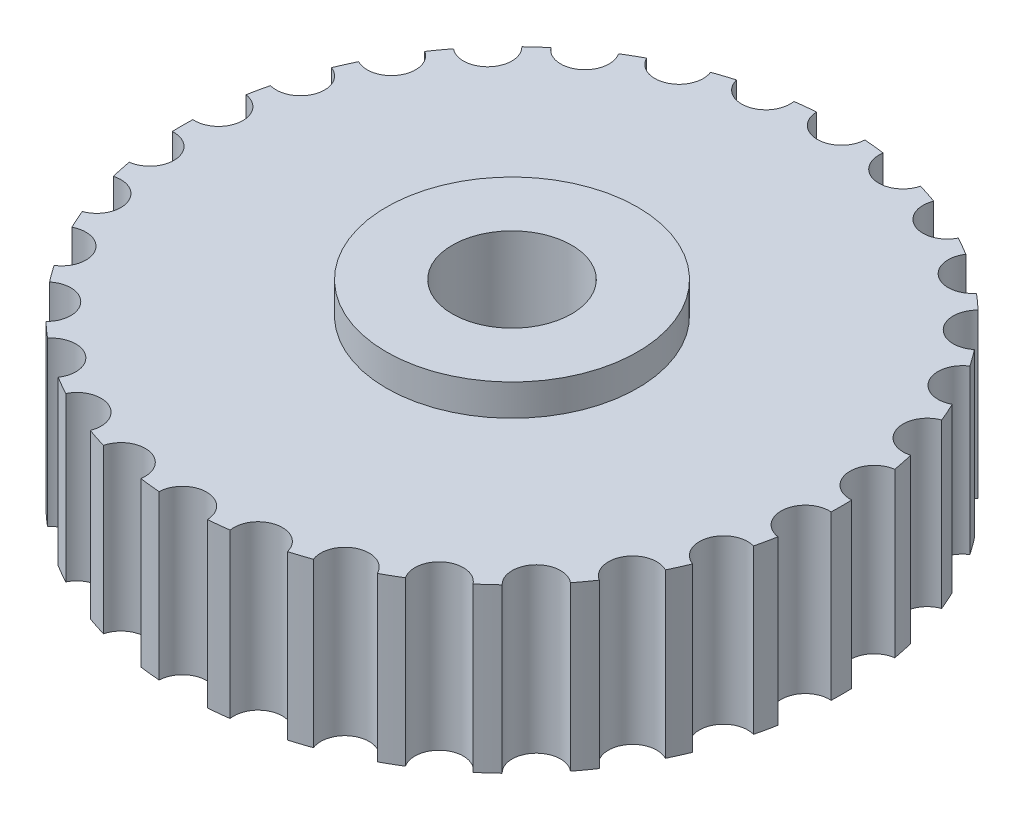
SolidWorks part; units mm, degrees
ref_plane "Спереди" through (0, 0, 0) normal (0, 0, 1) x (1, 0, 0)
ref_plane "Сверху" through (0, 0, 0) normal (0, 1, 0) x (1, 0, 0)
ref_plane "Справа" through (0, 0, 0) normal (1, 0, 0) x (0, 0, -1)
sketch "Эскиз1" plane through (0, 0, 0) normal (0, 1, 0) x (1, 0, 0)
  circle A0 centre (0, 0) radius 10.5
extrude "Бобышка-Вытянуть1" add sketch "Эскиз1" along normal blind 5.2
sketch "Эскиз2" plane through (0, 5.2, 0) normal (0, 1, 0) x (1, 0, 0)
  circle A0 centre (0, 0) radius 1.9
extrude "Вырез-Вытянуть1" cut sketch "Эскиз2" against normal through all
sketch "Эскиз3" plane through (0, 5.2, 0) normal (0, 1, 0) x (1, 0, 0)
  circle A0 centre (0, 0) radius 1.9
  circle A1 centre (0, 0) radius 4
extrude "Бобышка-Вытянуть2" add sketch "Эскиз3" along normal blind 1
sketch "Эскиз4" plane through (0, 5.2, 0) normal (0, 1, 0) x (1, 0, 0)
  line L0 (0, 0) -> (0, 10.5) construction
  circle A0 centre (0, 0) radius 10.5 construction
  circle A1 centre (0, 10.5) radius 0.7714
  circle A2 centre (2.1831, 10.2705) radius 0.7714
  circle A3 centre (4.2707, 9.5922) radius 0.7714
  circle A4 centre (6.1717, 8.4947) radius 0.7714
  circle A5 centre (7.803, 7.0259) radius 0.7714
  circle A6 centre (9.0933, 5.25) radius 0.7714
  circle A7 centre (9.9861, 3.2447) radius 0.7714
  circle A8 centre (10.4425, 1.0975) radius 0.7714
  circle A9 centre (10.4425, -1.0975) radius 0.7714
  circle A10 centre (9.9861, -3.2447) radius 0.7714
  circle A11 centre (9.0933, -5.25) radius 0.7714
  circle A12 centre (7.803, -7.0259) radius 0.7714
  circle A13 centre (6.1717, -8.4947) radius 0.7714
  circle A14 centre (4.2707, -9.5922) radius 0.7714
  circle A15 centre (2.1831, -10.2705) radius 0.7714
  circle A16 centre (0, -10.5) radius 0.7714
  circle A17 centre (-2.1831, -10.2705) radius 0.7714
  circle A18 centre (-4.2707, -9.5922) radius 0.7714
  circle A19 centre (-6.1717, -8.4947) radius 0.7714
  circle A20 centre (-7.803, -7.0259) radius 0.7714
  circle A21 centre (-9.0933, -5.25) radius 0.7714
  circle A22 centre (-9.9861, -3.2447) radius 0.7714
  circle A23 centre (-10.4425, -1.0975) radius 0.7714
  circle A24 centre (-10.4425, 1.0975) radius 0.7714
  circle A25 centre (-9.9861, 3.2447) radius 0.7714
  circle A26 centre (-9.0933, 5.25) radius 0.7714
  circle A27 centre (-7.803, 7.0259) radius 0.7714
  circle A28 centre (-6.1717, 8.4947) radius 0.7714
  circle A29 centre (-4.2707, 9.5922) radius 0.7714
  circle A30 centre (-2.1831, 10.2705) radius 0.7714
  dimension "D1" = 30
extrude "Вырез-Вытянуть3" cut sketch "Эскиз4" against normal through all
